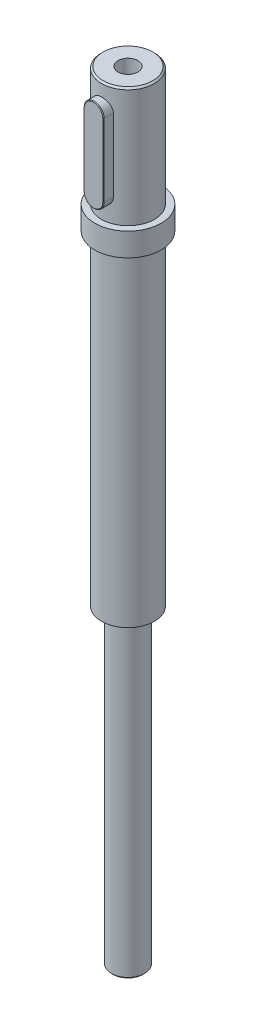
SolidWorks part; units mm, degrees
ref_plane "前视基准面" through (0, 0, 0) normal (0, 0, 1) x (1, 0, 0)
ref_plane "上视基准面" through (0, 0, 0) normal (0, 1, 0) x (1, 0, 0)
ref_plane "右视基准面" through (0, 0, 0) normal (1, 0, 0) x (0, 0, -1)
other "Configuration Table"
sketch "草图1" plane through (0, 0, 0) normal (0, 1, 0) x (1, 0, 0)
  circle A0 centre (0, 0) radius 2.5
  dimension "D1" = 5
extrude "凸台-拉伸1" add sketch "草图1" along normal blind 47
sketch "草图2" plane through (0, 0, 0) normal (0, 1, 0) x (1, 0, 0)
  circle A0 centre (0, 0) radius 4
  dimension "D1" = 8
extrude "凸台-拉伸2" add sketch "草图2" along normal blind 49 from surface at 47 starting at face at (0, 47, 2.5)
sketch "草图3" plane through (0, 0, 0) normal (0, 1, 0) x (1, 0, 0)
  circle A0 centre (0, 0) radius 5
  dimension "D1" = 10
extrude "凸台-拉伸3" add sketch "草图3" along normal blind 3.5 from surface at 96 starting at face at (0, 96, 4)
sketch "草图4" plane through (0, 0, 0) normal (0, 1, 0) x (1, 0, 0)
  circle A0 centre (0, 0) radius 4
  dimension "D1" = 8
extrude "凸台-拉伸4" add sketch "草图4" along normal blind 18 from surface at 99.5 starting at face at (0, 99.5, 5)
sketch "草图6" plane through (0, 0, 0) normal (0, 1, 0) x (1, 0, 0)
  circle A0 centre (0, 0) radius 1.5
  point P0 (0, 0)
  dimension "D1" = 3
sketch "草图11" plane through (0, 0, 0) normal (0, 0, 1) x (1, 0, 0)
  line L0 (-4, 117.5) -> (4, 99.5) construction
  line L1 (-4, 117.5) -> (4, 117.5) construction
  line L2 (-4, 117.5) -> (-4, 99.5) construction
  line L3 (-4, 99.5) -> (4, 99.5) construction
  line L4 (4, 117.5) -> (4, 99.5) construction
  line L5 (4, 117.5) -> (-4, 99.5) construction
  line L6 (0, 103) -> (0, 114) construction
  line L7 (-1.5, 103) -> (-1.5, 114)
  line L8 (1.5, 103) -> (1.5, 114)
  arc A0 (-1.5, 103) -> (1.5, 103) centre (0, 103) ccw
  arc A1 (1.5, 114) -> (-1.5, 114) centre (0, 114) ccw
  point P8 (0, 108.5)
  dimension "D1" = 1.5
  dimension "D2" = 11
extrude "凸台-拉伸5" add sketch "草图11" along normal blind 3 from offset 2.2
chamfer "倒角1" distance 0.25 angle 45 2 edges at (0, 117.5, 4) (0, 0, 2.5)
chamfer "倒角2" distance 0.1 angle 45 4 edges at (0, 115.5, 5.2) (-1.5, 108.5, 5.2) (0, 101.5, 5.2) (1.5, 108.5, 5.2)
extrude "切除-拉伸1" cut sketch "草图6" against normal blind 10 from surface at 117.5 starting at face at (0, 117.5, 3.75)
